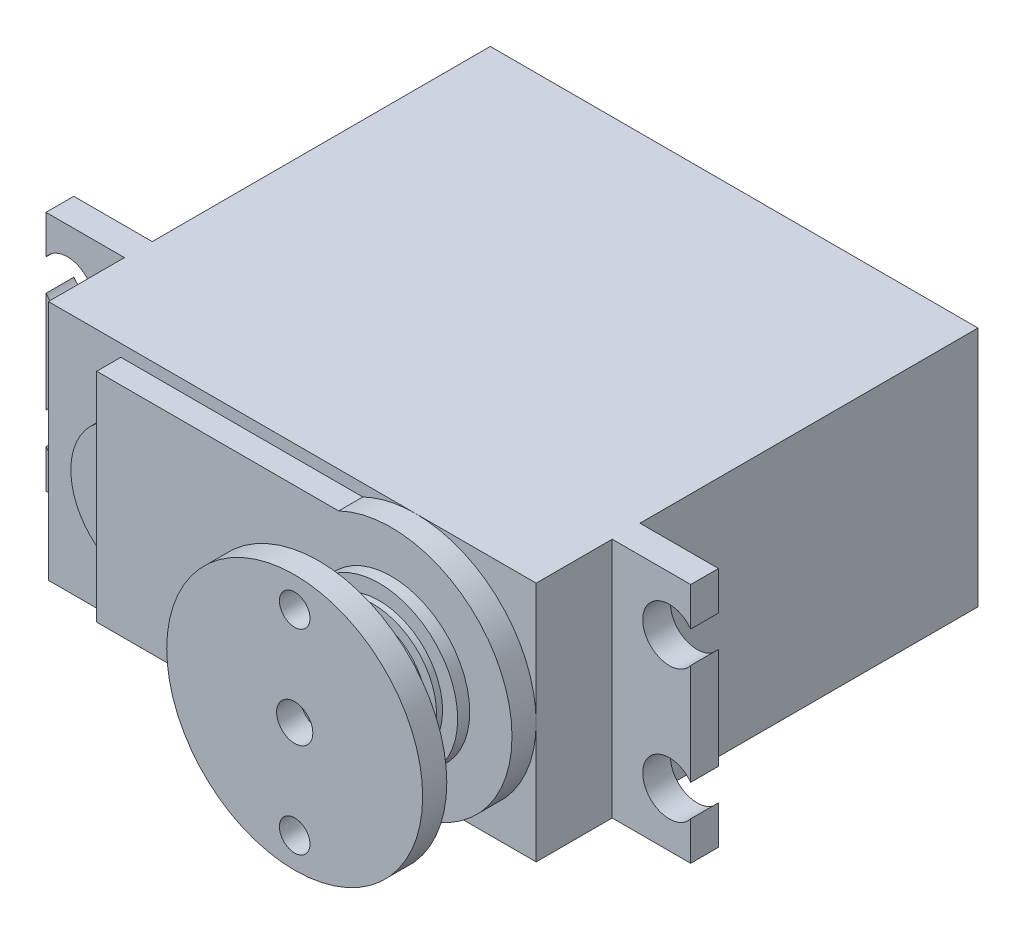
SolidWorks part; units mm, degrees
ref_plane "Front Plane" through (0, 0, 0) normal (0, 0, 1) x (1, 0, 0)
ref_plane "Top Plane" through (0, 0, 0) normal (0, 1, 0) x (1, 0, 0)
ref_plane "Right Plane" through (0, 0, 0) normal (1, 0, 0) x (0, 0, -1)
sketch "Sketch1" plane through (0, 0, 0) normal (0, 0, 1) x (1, 0, 0)
  line L1 (-20.2, 10) -> (20.2, 10)
  line L2 (-20.2, 10) -> (-20.2, -10)
  line L3 (-20.2, -10) -> (20.2, -10)
  line L4 (20.2, 10) -> (20.2, -10)
  line L5 (-20.2, 10) -> (20.2, -10) construction
  line L6 (-20.2, -10) -> (20.2, 10) construction
  point P0 (0, 0)
  dimension "D1" = 40.4
  dimension "D2" = 20
extrude "Boss-Extrude1" add sketch "Sketch1" along normal blind 36.6
sketch "Sketch2" plane through (20.2, 0, 0) normal (1, 0, 0) x (0, 0, -1)
  line L0 (-28, -10) -> (-28, 10)
  line L1 (0, -10) -> (0, 10) construction
  line L2 (-36.6, 10) -> (0, 10) construction
  line L3 (-36.6, -10) -> (0, -10) construction
  line L5 (-28, -10) -> (-30.3, -10)
  line L6 (-28, -10) -> (-28, 10)
  line L7 (-28, 10) -> (-30.3, 10)
  line L8 (-30.3, -10) -> (-30.3, 10)
  line M4 (0, 10) -> (-36.6, 10)
  line M6 (-36.6, -10) -> (0, -10)
  dimension "D1" = 28
  dimension "D2" = 2.3
extrude "Boss-Extrude2" add sketch "Sketch2" along normal blind 6.5 contours L8 L0 M6 M4
sketch "Sketch3" plane through (0, 0, 30.3) normal (0, 0, 1) x (1, 0, 0)
  line L0 (24.9292, 5.5) -> (24.9292, -5.5) construction
  line L1 (24.9292, 0) -> (28.3576, 0) construction
  line L2 (26.7, -10) -> (26.7, 10) construction
  line L3 (20.2, -10) -> (20.2, 10) construction
  circle A0 centre (24.9292, -5.5) radius 2.2
  circle A1 centre (24.9292, 5.5) radius 2.2
  point P8 (26.7, 0)
  point P9 (24.9292, -5.5)
  dimension "D1" = 4.4
  dimension "D2" = 11
  dimension "D3" = 4.7292
extrude "Cut-Extrude1" cut sketch "Sketch3" against normal blind 6.5
mirror "Mirror1" about plane through (0, 0, 0) normal (1, 0, 0) of "Cut-Extrude1", "Boss-Extrude2"
sketch "Sketch5" plane through (0, 0, 36.6) normal (0, 0, 1) x (1, 0, 0)
  line L0 (20.2, -10) -> (20.2, 10) construction
  line L1 (-20.2, -10) -> (20.2, -10) construction
  line L2 (-20.2, 10) -> (-20.2, -10) construction
  line L3 (-14.2, 9) -> (5.8411, 9)
  line L4 (-14.2, 9) -> (-14.2, -9)
  line L5 (-14.2, -9) -> (5.8411, -9)
  line L6 (5.8411, 9) -> (5.8411, -9)
  line L8 (20.2, 10) -> (-20.2, 10) construction
  circle A0 centre (10.2, 0) radius 10
  arc A1 (-14.2, 5.1007) -> (-14.2, -4.3993) centre (-11.2524, 0.3507) ccw
  point P14 (5.8411, 0)
  point P15 (-10.7508, 0)
  dimension "D1" = 6
  dimension "D3" = 9.5
  dimension "D4" = 5.5902
  dimension "D2" = 1
  dimension "D5" = 4.8993
extrude "Boss-Extrude4" add sketch "Sketch5" along normal blind 2 contours A0 L3 L4 L5 | A0 L6 | L6 A0
sketch "Sketch6" plane through (0, 0, 36.6) normal (0, 0, 1) x (1, 0, 0)
  line L4 (5.8411, 9) -> (-14.2, 9)
  line L5 (5.8411, -9) -> (5.8411, 9)
  line L6 (-14.2, -9) -> (5.8411, -9)
  line L7 (-14.2, 9) -> (-14.2, -9)
  line L8 (5.8411, 9) -> (-14.2, 9)
  line L9 (5.8411, -9) -> (5.8411, 9)
  line L10 (-14.2, -9) -> (5.8411, -9)
  line L11 (-14.2, 9) -> (-14.2, -9)
  arc A0 (-14.2, 5.1007) -> (-14.2, -4.3993) centre (-11.2524, 0.3507) ccw construction
  circle A1 centre (10.2, 0) radius 10
  circle A2 centre (10.2, 0) radius 10
  arc A3 (-14.2, 5.1007) -> (-14.2, -4.3993) centre (-11.2524, 0.3507) ccw
  dimension "D1" = 0
  dimension "D2" = 0
extrude "Boss-Extrude5" add sketch "Sketch6" along normal blind 1.5 contours L11 A3
sketch "Sketch7" plane through (0, 0, 38.6) normal (0, 0, 1) x (1, 0, 0)
  circle A0 centre (10.2, 0) radius 6.5
  dimension "D1" = 13
extrude "Boss-Extrude6" add sketch "Sketch7" along normal blind 1
sketch "Sketch9" plane through (0, 0, 39.6) normal (0, 0, 1) x (1, 0, 0)
  circle A0 centre (10.2, 0) radius 5.25
  dimension "D1" = 10.5
extrude "Boss-Extrude7" add sketch "Sketch9" along normal blind 0.5
sketch "Sketch10" plane through (0, 0, 40.1) normal (0, 0, 1) x (1, 0, 0)
  circle A0 centre (10.2, 0) radius 4.4
  dimension "D1" = 8.8
extrude "Boss-Extrude8" add sketch "Sketch10" along normal blind 4.5
sketch "Sketch11" plane through (0, 0, 44.6) normal (0, 0, 1) x (1, 0, 0)
  circle A0 centre (10.2, 0) radius 10.6
  dimension "D1" = 21.2
extrude "Boss-Extrude9" add sketch "Sketch11" along normal blind 2
sketch "Sketch12" plane through (0, 0, 46.6) normal (0, 0, 1) x (1, 0, 0)
  circle A0 centre (10.2, 0) radius 1.5
  circle A2 centre (10.2, 0) radius 8.1
  circle A3 centre (10.2, 0) radius 10.6
  circle A4 centre (10.2, 0) radius 10.6
  circle A5 centre (10.2, -8.1) radius 1.2648
  dimension "D1" = 3
  dimension "D2" = 0
  dimension "D4" = 2.5296
  dimension "D3" = 2.5
extrude "Cut-Extrude2" cut sketch "Sketch12" against normal blind 2 contours A2 A5 | A2 A5 | A0
pattern_circular "CirPattern1" count 2 over 360 about axis through (10.2, 0, 0) along (0, 0, 1) of "Cut-Extrude2"
